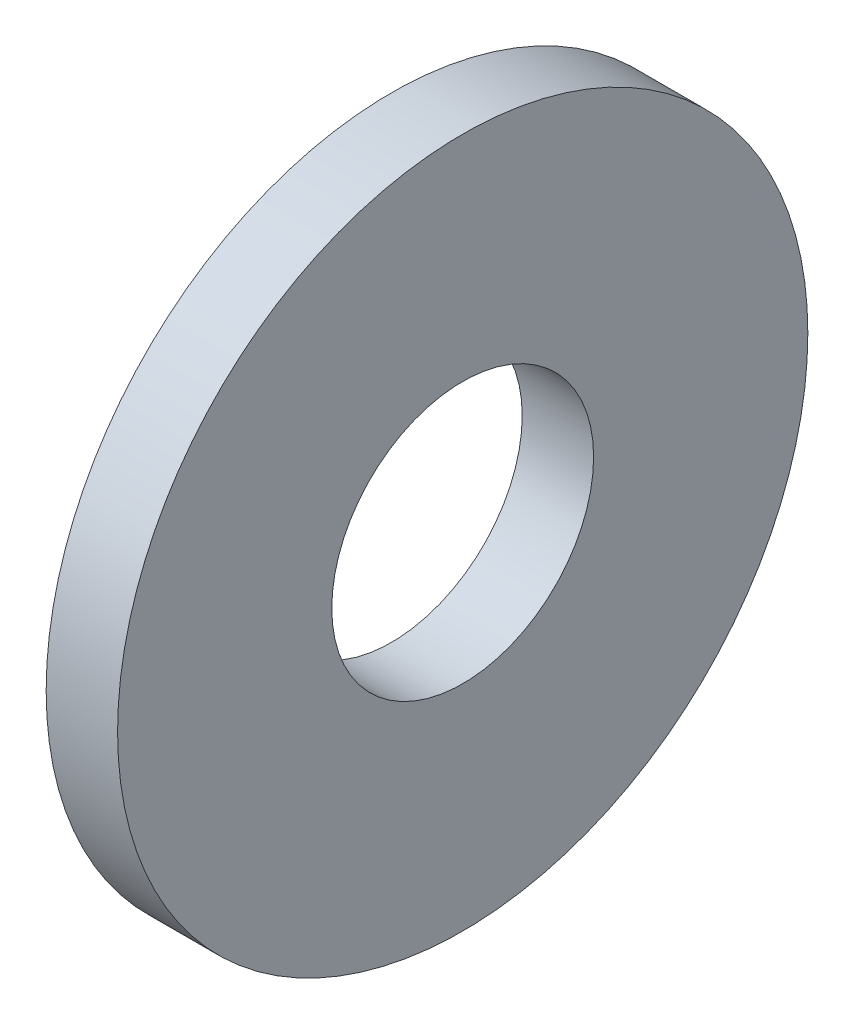
SolidWorks part; units mm, degrees
ref_plane "Plane1" through (0, 0, 0) normal (0, 0, 1) x (1, 0, 0)
ref_plane "Plane2" through (0, 0, 0) normal (0, 1, 0) x (1, 0, 0)
ref_plane "Plane3" through (0, 0, 0) normal (1, 0, 0) x (0, 0, -1)
sketch "Sketch1" plane through (0, 0, 0) normal (1, 0, 0) x (0, 0, -1)
  circle A0 centre (0, 0) radius 5.5
  circle A1 centre (0, 0) radius 14.5
  dimension "Insid_Dia" = 11
  dimension "OutsideDia" = 29
extrude "Base-Extrude" add sketch "Sketch1" along normal blind 3
